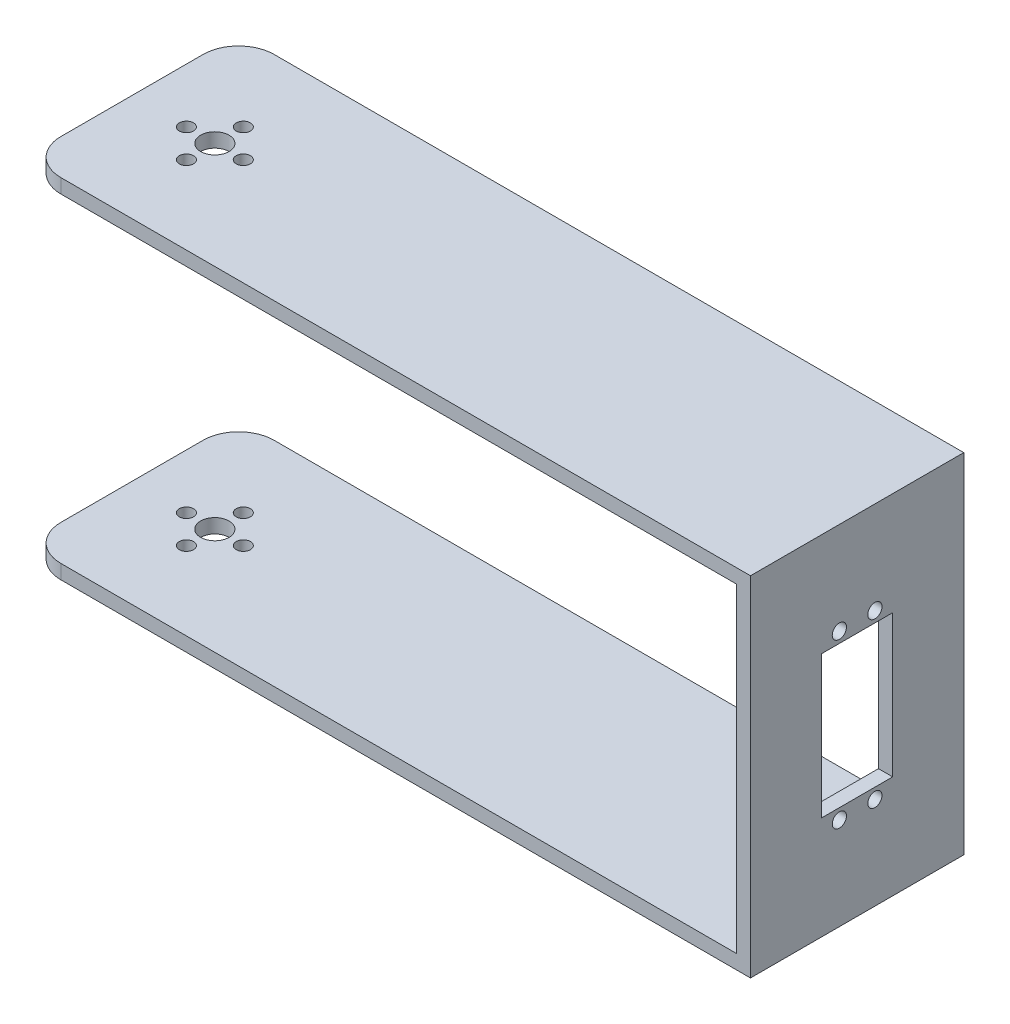
SolidWorks part; units mm, degrees
ref_plane "Ön Düzlem" through (0, 0, 0) normal (0, 0, 1) x (1, 0, 0)
ref_plane "Üst Düzlem" through (0, 0, 0) normal (0, 1, 0) x (1, 0, 0)
ref_plane "Sağ Düzlem" through (0, 0, 0) normal (1, 0, 0) x (0, 0, -1)
sketch "Çizim1" plane through (0, 0, 0) normal (0, 0, 1) x (1, 0, 0)
  line L0 (0, 0) -> (200, 0)
  line L1 (200, 0) -> (200, 90)
  line L2 (200, 90) -> (0, 90)
  dimension "D1" = 90
  dimension "D2" = 200
extrude "Ekstrüzyon-İnce1" add sketch "Çizim1" along normal blind 60 thin
fillet "Radyus1" radius 10 4 edges at (0, -2, 60) (0, -2, 0) (0, 92, 0) (0, 92, 60)
sketch "Çizim2" plane through (0, 94, 0) normal (0, 1, 0) x (1, 0, 0)
  circle A0 centre (23.3181, -30) radius 4
  circle A1 centre (23.3181, -22) radius 2
  circle A2 centre (23.3181, -38) radius 2
  circle A3 centre (31.3181, -30) radius 2
  circle A4 centre (15.3181, -30) radius 2
  dimension "D1" = 8
  dimension "D3" = 4
  dimension "D5" = 4
  dimension "D2" = 8
  dimension "D4" = 8
extrude "Kes-Ekstrüzyon1" cut sketch "Çizim2" against normal up to next
ref_plane "Düzlem1" through (0, 45, 0) normal (0, 1, 0) x (1, 0, 0)
mirror "Aynalama1" about plane through (0, 45, 0) normal (0, 1, 0) of "Kes-Ekstrüzyon1"
sketch "Çizim3" plane through (204, 0, 0) normal (1, 0, 0) x (0, 0, -1)
  line L0 (-60, -4) -> (0, -4) construction
  line L1 (-20, 25) -> (-40, 25)
  line L2 (-20, 25) -> (-20, 65)
  line L3 (-20, 65) -> (-40, 65)
  line L4 (-40, 25) -> (-40, 65)
  line L7 (0, -4) -> (0, 94) construction
  line L10 (-40, 45) -> (-20, 45) construction
  circle A0 centre (-25, 68) radius 2
  circle A1 centre (-35, 68) radius 2
  circle A2 centre (-25, 22) radius 2
  circle A3 centre (-35, 22) radius 2
  dimension "D7" = 4
  dimension "D1" = 40
  dimension "D2" = 20
  dimension "D3" = 29
  dimension "D4" = 20
extrude "Kes-Ekstrüzyon2" cut sketch "Çizim3" against normal up to next
